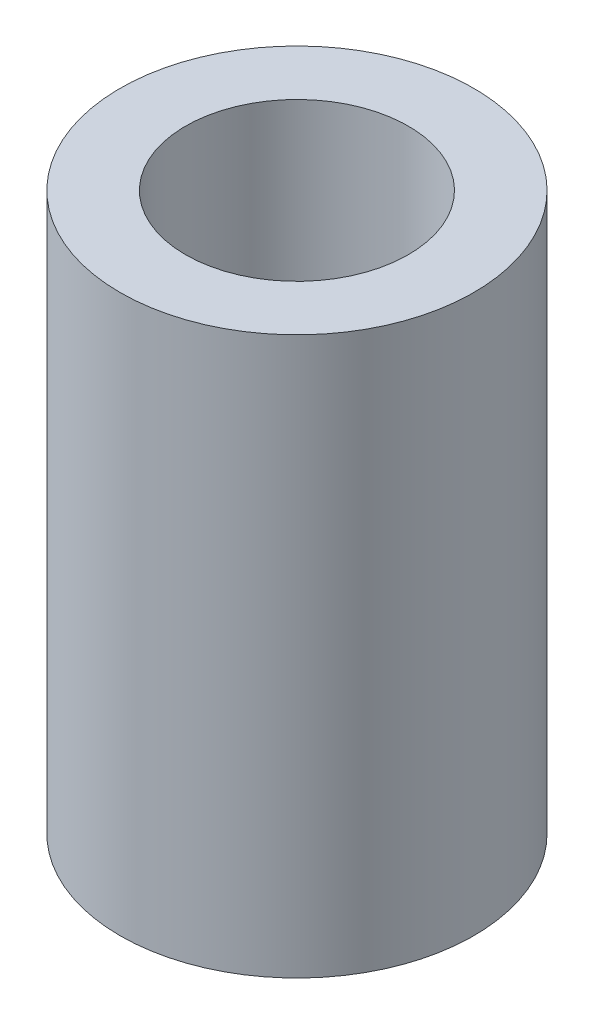
SolidWorks part; units mm, degrees
ref_plane "Front Plane" through (0, 0, 0) normal (0, 0, 1) x (1, 0, 0)
ref_plane "Top Plane" through (0, 0, 0) normal (0, 1, 0) x (1, 0, 0)
ref_plane "Right Plane" through (0, 0, 0) normal (1, 0, 0) x (0, 0, -1)
sketch "Sketch1" plane through (0, 0, 0) normal (0, 1, 0) x (1, 0, 0)
  circle A0 centre (0, 0) radius 4.7625
  circle A1 centre (0, 0) radius 3
  dimension "D1" = 9.525
  dimension "D2" = 6
extrude "Boss-Extrude1" add sketch "Sketch1" along normal blind 15
